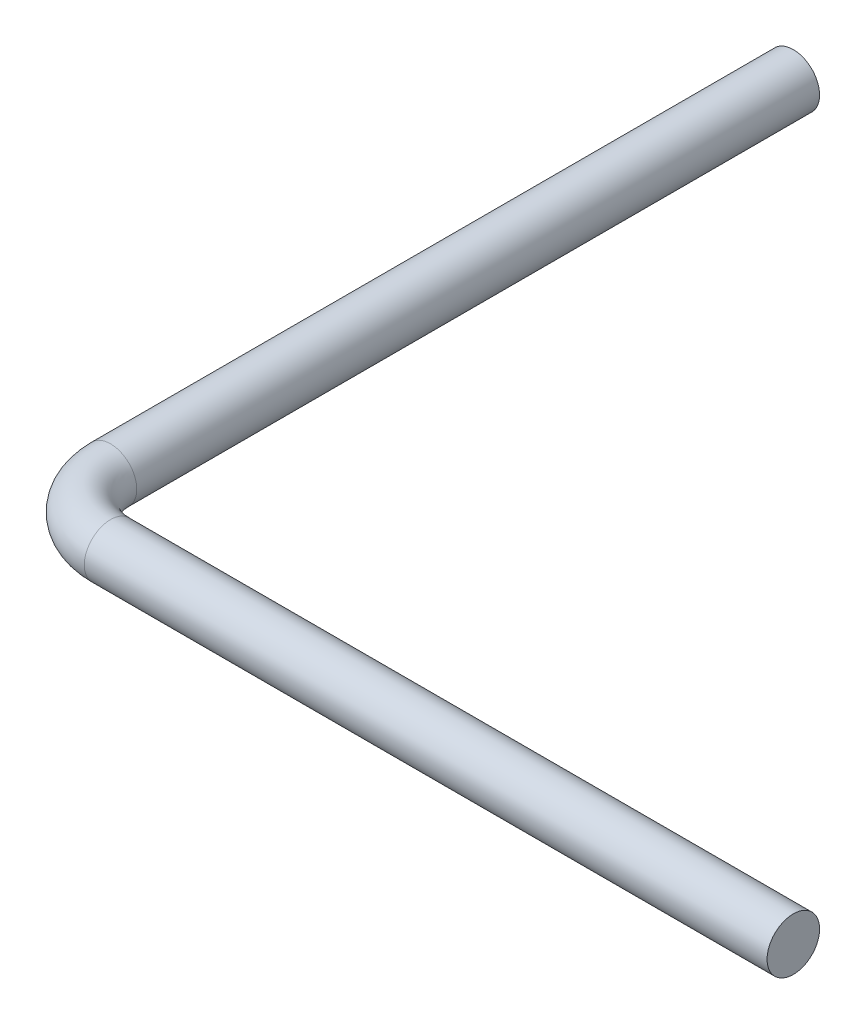
SolidWorks part; units mm, degrees
ref_plane "正面" through (0, 0, 0) normal (0, 0, 1) x (1, 0, 0)
ref_plane "平面" through (0, 0, 0) normal (0, 1, 0) x (1, 0, 0)
ref_plane "右側面" through (0, 0, 0) normal (1, 0, 0) x (0, 0, -1)
sketch "ｽｹｯﾁ1" plane through (0, 0, 0) normal (0, 0, 1) x (1, 0, 0)
  circle A0 centre (0, 0) radius 2
  dimension "D1" = 4
extrude "ﾎﾞｽ - 押し出し1" add sketch "ｽｹｯﾁ1" along normal blind 50
sketch "ｽｹｯﾁ2" plane through (0, 0, 0) normal (0, 1, 0) x (1, 0, 0)
  line L0 (0, -50) -> (0, -52)
  line L1 (-2, -50) -> (2, -50) construction
  line L2 (5, -57) -> (57, -57)
  arc A0 (0, -52) -> (5, -57) centre (5, -52) ccw
  dimension "D1" = 5
  dimension "D2" = 2
  dimension "D3" = 52
sketch "ｽｹｯﾁ3" plane through (0, 0, 50) normal (0, 0, 1) x (1, 0, 0)
  circle A1 centre (0, 0) radius 2
  circle A2 centre (0, 0) radius 2
  dimension "D1" = 0
sweep "ｽｲｰﾌﾟ1" add profiles "ｽｹｯﾁ3" path "ｽｹｯﾁ2"
